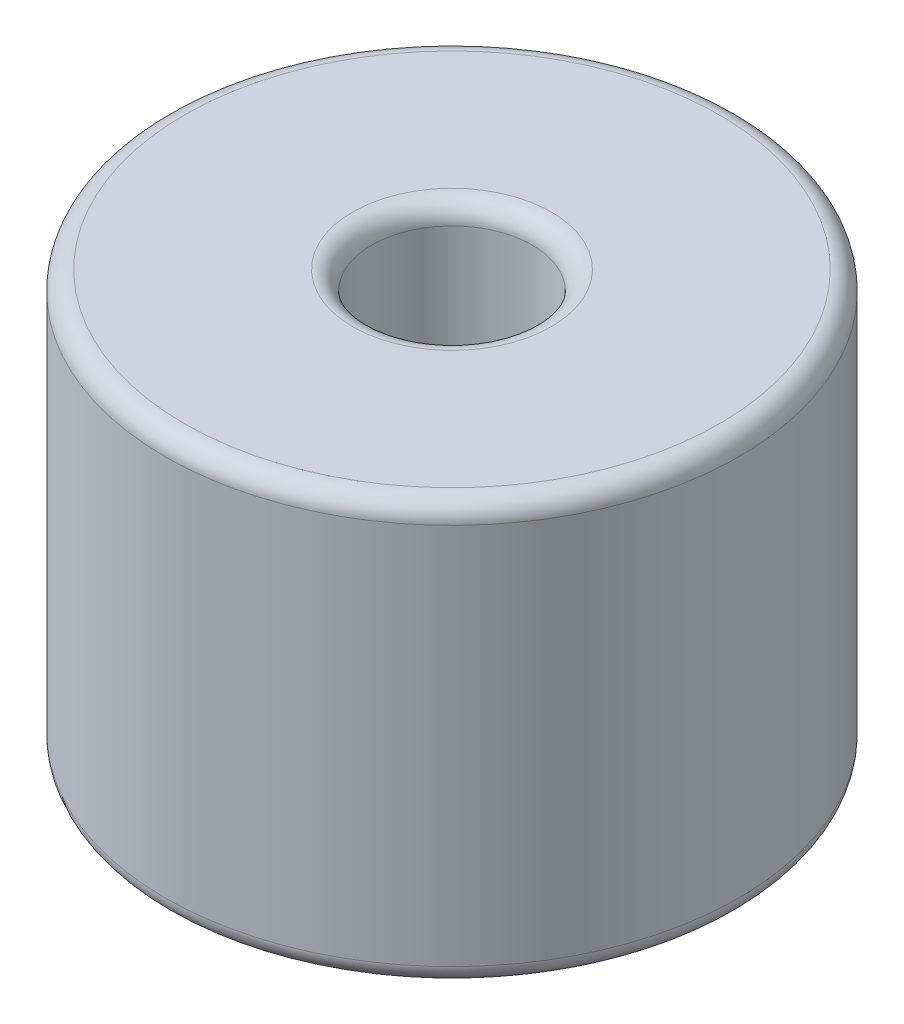
SolidWorks part; units mm, degrees
ref_plane "Front Plane" through (0, 0, 0) normal (0, 0, 1) x (1, 0, 0)
ref_plane "Top Plane" through (0, 0, 0) normal (0, 1, 0) x (1, 0, 0)
ref_plane "Right Plane" through (0, 0, 0) normal (1, 0, 0) x (0, 0, -1)
sketch "Sketch1" plane through (0, 0, 0) normal (0, 1, 0) x (1, 0, 0)
  circle A0 centre (0, 0) radius 2.1
  circle A1 centre (0, 0) radius 7.5
  dimension "D1" = 4.2
  dimension "D2" = 15
extrude "Boss-Extrude1" add sketch "Sketch1" along normal blind 11
fillet "Fillet1" radius 0.5 4 edges at (0, 0, 2.1) (0, 11, 2.1) (0, 0, 7.5) (0, 11, 7.5)
